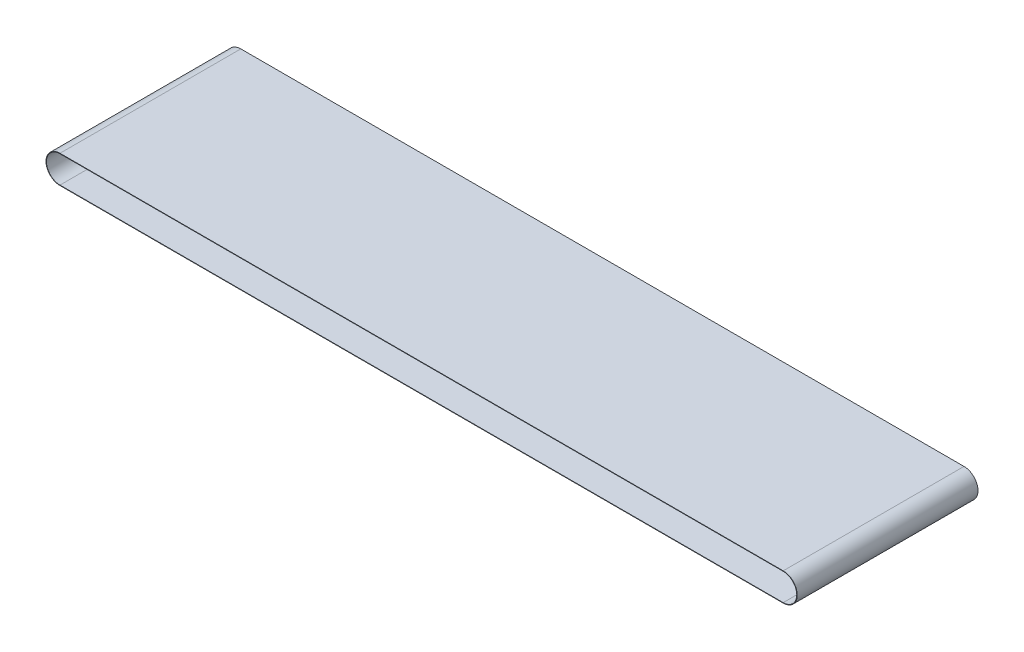
SolidWorks part; units mm, degrees
material "Rubber"
ref_plane "Front Plane" through (0, 0, 0) normal (0, 0, 1) x (1, 0, 0)
ref_plane "Top Plane" through (0, 0, 0) normal (0, 1, 0) x (1, 0, 0)
ref_plane "Right Plane" through (0, 0, 0) normal (1, 0, 0) x (0, 0, -1)
sketch "Sketch1" plane through (0, 0, 0) normal (0, 0, 1) x (1, 0, 0)
  line L0 (0, 0) -> (2000, 0) construction
  line L1 (0, 37.5) -> (2000, 37.5)
  line L2 (0, -37.5) -> (2000, -37.5)
  line L3 (0, -38.7) -> (2000, -38.7)
  line L4 (0, 38.7) -> (2000, 38.7)
  arc A0 (0, 37.5) -> (0, -37.5) centre (0, 0) ccw
  arc A1 (2000, -37.5) -> (2000, 37.5) centre (2000, 0) ccw
  arc A2 (0, 38.7) -> (0, -38.7) centre (0, 0) ccw
  arc A3 (2000, -38.7) -> (2000, 38.7) centre (2000, 0) ccw
  dimension "Overall_Length" = 2000
  dimension "D2" = 75
  dimension "D3" = 1.2
extrude "Boss-Extrude1" add sketch "Sketch1" along normal mid plane 500
